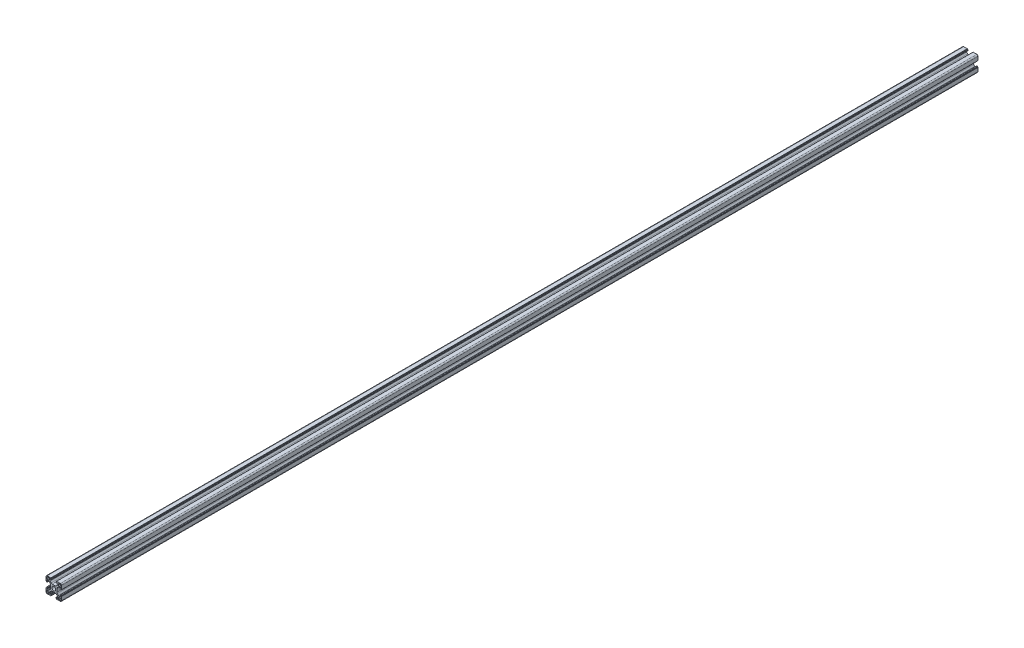
SolidWorks part; units mm, degrees
material "1060 Сплав"
ref_plane "Спереди" through (0, 0, 0) normal (0, 0, 1) x (1, 0, 0)
ref_plane "Сверху" through (0, 0, 0) normal (0, 1, 0) x (1, 0, 0)
ref_plane "Справа" through (0, 0, 0) normal (1, 0, 0) x (0, 0, -1)
sketch "Эскиз1" plane through (0, 0, 0) normal (0, 0, 1) x (1, 0, 0)
  line L0 (9.3595, 9.1357) -> (6.3595, 6.1357) construction
  line L1 (0.2595, 4.0357) -> (2.1582, 4.0357)
  line L2 (0.2595, 0.0357) -> (10.2595, 10.0357) construction
  line L3 (7.8595, 7.6357) -> (6.3595, 9.1357) construction
  line L4 (3.5725, 4.6215) -> (4.8737, 5.9227)
  line L5 (7.1595, 6.1357) -> (8.5595, 6.1357)
  line L6 (6.3595, 6.9357) -> (6.3595, 8.3357)
  line L7 (8.5595, 9.1357) -> (7.1595, 9.1357)
  line L8 (5.4595, 8.2357) -> (5.4595, 7.3369)
  line L9 (4.0227, 8.1089) -> (4.503, 8.5893)
  line L10 (3.4595, 9.5848) -> (3.9595, 9.5848)
  line L11 (3.8459, 8.0357) -> (3.5595, 8.0357)
  line L12 (4.8566, 8.7357) -> (4.9595, 8.7357)
  line L13 (3.9595, 9.8857) -> (3.9595, 9.5848)
  line L14 (3.3095, 9.4348) -> (3.3095, 8.2857)
  line L15 (8.7595, 10.0357) -> (4.1095, 10.0357)
  line L16 (9.3595, 8.3357) -> (9.3595, 6.9357)
  line L17 (10.2595, 8.5357) -> (10.2595, 3.8857)
  line L18 (9.6585, 3.0857) -> (8.5095, 3.0857)
  line L19 (10.1095, 3.7357) -> (9.8085, 3.7357)
  line L20 (8.9595, 4.6328) -> (8.9595, 4.7357)
  line L21 (8.2595, 3.6221) -> (8.2595, 3.3357)
  line L22 (9.8085, 3.2357) -> (9.8085, 3.7357)
  line L23 (8.3327, 3.7989) -> (8.813, 4.2793)
  line L24 (8.4595, 5.2357) -> (7.5607, 5.2357)
  line L25 (4.8452, 3.3487) -> (6.1465, 4.6499)
  line L26 (4.2595, 0.0357) -> (4.2595, 1.9345)
  line L27 (4.2595, 0.0357) -> (4.2595, -1.8631)
  line L28 (4.8452, -3.2773) -> (6.1465, -4.5785)
  line L29 (6.3595, -6.8643) -> (6.3595, -8.2643)
  line L30 (7.1595, -6.0643) -> (8.5595, -6.0643)
  line L31 (9.3595, -8.2643) -> (9.3595, -6.8643)
  line L32 (8.4595, -5.1643) -> (7.5607, -5.1643)
  line L33 (8.3327, -3.7275) -> (8.813, -4.2079)
  line L34 (9.8085, -3.1643) -> (9.8085, -3.6643)
  line L35 (8.2595, -3.5507) -> (8.2595, -3.2643)
  line L36 (8.9595, -4.5614) -> (8.9595, -4.6643)
  line L37 (10.1095, -3.6643) -> (9.8085, -3.6643)
  line L38 (9.6585, -3.0143) -> (8.5095, -3.0143)
  line L39 (10.2595, -8.4643) -> (10.2595, -3.8143)
  line L40 (8.5595, -9.0643) -> (7.1595, -9.0643)
  line L41 (8.7595, -9.9643) -> (4.1095, -9.9643)
  line L42 (3.3095, -9.3634) -> (3.3095, -8.2143)
  line L43 (3.9595, -9.8143) -> (3.9595, -9.5134)
  line L44 (4.8566, -8.6643) -> (4.9595, -8.6643)
  line L45 (3.8459, -7.9643) -> (3.5595, -7.9643)
  line L46 (3.4595, -9.5134) -> (3.9595, -9.5134)
  line L47 (4.0227, -8.0375) -> (4.503, -8.5179)
  line L48 (5.4595, -8.1643) -> (5.4595, -7.2655)
  line L49 (3.5725, -4.5501) -> (4.8737, -5.8513)
  line L50 (0.2595, -3.9643) -> (2.1582, -3.9643)
  line L51 (9.3595, -9.0643) -> (6.3595, -6.0643) construction
  line L52 (0.2595, 0.0357) -> (10.2595, -9.9643) construction
  line L53 (7.8595, -7.5643) -> (9.3595, -6.0643) construction
  line L54 (0.2595, -3.9643) -> (-1.6393, -3.9643)
  line L55 (-3.0535, -4.5501) -> (-4.3548, -5.8513)
  line L56 (-6.6405, -6.0643) -> (-8.0405, -6.0643)
  line L57 (-5.8405, -6.8643) -> (-5.8405, -8.2643)
  line L58 (-8.0405, -9.0643) -> (-6.6405, -9.0643)
  line L59 (-4.9405, -8.1643) -> (-4.9405, -7.2655)
  line L60 (-3.5038, -8.0375) -> (-3.9841, -8.5179)
  line L61 (-2.9405, -9.5134) -> (-3.4405, -9.5134)
  line L62 (-3.327, -7.9643) -> (-3.0405, -7.9643)
  line L63 (-4.3376, -8.6643) -> (-4.4405, -8.6643)
  line L64 (-3.4405, -9.8143) -> (-3.4405, -9.5134)
  line L65 (-2.7905, -9.3634) -> (-2.7905, -8.2143)
  line L66 (-8.2405, -9.9643) -> (-3.5905, -9.9643)
  line L67 (-8.8405, -8.2643) -> (-8.8405, -6.8643)
  line L68 (-9.7405, -8.4643) -> (-9.7405, -3.8143)
  line L69 (-9.1396, -3.0143) -> (-7.9905, -3.0143)
  line L70 (-9.5905, -3.6643) -> (-9.2896, -3.6643)
  line L71 (-8.4405, -4.5614) -> (-8.4405, -4.6643)
  line L72 (-7.7405, -3.5507) -> (-7.7405, -3.2643)
  line L73 (-9.2896, -3.1643) -> (-9.2896, -3.6643)
  line L74 (-7.8138, -3.7275) -> (-8.2941, -4.2079)
  line L75 (-7.9405, -5.1643) -> (-7.0418, -5.1643)
  line L76 (-4.3263, -3.2773) -> (-5.6275, -4.5785)
  line L77 (-3.7405, 0.0357) -> (-3.7405, -1.8631)
  line L78 (-8.8405, -9.0643) -> (-5.8405, -6.0643) construction
  line L79 (0.2595, 0.0357) -> (-9.7405, -9.9643) construction
  line L80 (-7.3405, -7.5643) -> (-5.8405, -9.0643) construction
  line L81 (-3.7405, 0.0357) -> (-3.7405, 1.9345)
  line L82 (-4.3263, 3.3487) -> (-5.6275, 4.6499)
  line L83 (-5.8405, 6.9357) -> (-5.8405, 8.3357)
  line L84 (-6.6405, 6.1357) -> (-8.0405, 6.1357)
  line L85 (-8.8405, 8.3357) -> (-8.8405, 6.9357)
  line L86 (-7.9405, 5.2357) -> (-7.0418, 5.2357)
  line L87 (-7.8138, 3.7989) -> (-8.2941, 4.2793)
  line L88 (-9.2896, 3.2357) -> (-9.2896, 3.7357)
  line L89 (-7.7405, 3.6221) -> (-7.7405, 3.3357)
  line L90 (-8.4405, 4.6328) -> (-8.4405, 4.7357)
  line L91 (-9.5905, 3.7357) -> (-9.2896, 3.7357)
  line L92 (-9.1396, 3.0857) -> (-7.9905, 3.0857)
  line L93 (-9.7405, 8.5357) -> (-9.7405, 3.8857)
  line L94 (-8.0405, 9.1357) -> (-6.6405, 9.1357)
  line L95 (-8.2405, 10.0357) -> (-3.5905, 10.0357)
  line L96 (-2.7905, 9.4348) -> (-2.7905, 8.2857)
  line L97 (-3.4405, 9.8857) -> (-3.4405, 9.5848)
  line L98 (-4.3376, 8.7357) -> (-4.4405, 8.7357)
  line L99 (-3.327, 8.0357) -> (-3.0405, 8.0357)
  line L100 (-2.9405, 9.5848) -> (-3.4405, 9.5848)
  line L101 (-3.5038, 8.1089) -> (-3.9841, 8.5893)
  line L102 (-4.9405, 8.2357) -> (-4.9405, 7.3369)
  line L103 (-3.0535, 4.6215) -> (-4.3548, 5.9227)
  line L104 (0.2595, 4.0357) -> (-1.6393, 4.0357)
  line L105 (-11.5046, 0.0357) -> (11.7638, 0.0357) construction
  line L106 (-8.8405, 9.1357) -> (-5.8405, 6.1357) construction
  line L107 (0.2595, -12.0507) -> (0.2595, 10.7546) construction
  line L108 (0.2595, 0.0357) -> (-9.7405, 10.0357) construction
  line L109 (-7.3405, 7.6357) -> (-8.8405, 6.1357) construction
  arc A0 (9.3595, 8.3357) -> (8.5595, 9.1357) centre (8.5595, 8.3357) ccw
  arc A1 (7.1595, 9.1357) -> (6.3595, 8.3357) centre (7.1595, 8.3357) ccw
  arc A2 (7.1595, 6.1357) -> (6.3595, 6.9357) centre (7.1595, 6.9357) cw
  arc A3 (8.7595, 10.0357) -> (10.2595, 8.5357) centre (8.7595, 8.5357) cw
  arc A4 (3.4595, 9.5848) -> (3.3095, 9.4348) centre (3.4595, 9.4348) ccw
  arc A5 (4.1095, 10.0357) -> (3.9595, 9.8857) centre (4.1095, 9.8857) ccw
  arc A6 (3.8459, 8.0357) -> (4.0227, 8.1089) centre (3.8459, 8.2857) ccw
  arc A7 (3.5595, 8.0357) -> (3.3095, 8.2857) centre (3.5595, 8.2857) cw
  arc A8 (4.503, 8.5893) -> (4.8566, 8.7357) centre (4.8566, 8.2357) cw
  arc A9 (4.9595, 8.7357) -> (5.4595, 8.2357) centre (4.9595, 8.2357) cw
  arc A10 (2.7595, 0.0357) -> (0.2595, 2.5357) centre (0.2595, 0.0357) ccw
  arc A11 (2.1582, 4.0357) -> (3.5725, 4.6215) centre (2.1582, 6.0357) ccw
  arc A12 (5.4595, 7.3369) -> (4.8737, 5.9227) centre (3.4595, 7.3369) cw
  arc A13 (9.3595, 6.9357) -> (8.5595, 6.1357) centre (8.5595, 6.9357) cw
  arc A14 (8.9595, 4.7357) -> (8.4595, 5.2357) centre (8.4595, 4.7357) ccw
  arc A15 (8.813, 4.2793) -> (8.9595, 4.6328) centre (8.4595, 4.6328) ccw
  arc A16 (8.2595, 3.3357) -> (8.5095, 3.0857) centre (8.5095, 3.3357) ccw
  arc A17 (8.2595, 3.6221) -> (8.3327, 3.7989) centre (8.5095, 3.6221) cw
  arc A18 (10.2595, 3.8857) -> (10.1095, 3.7357) centre (10.1095, 3.8857) cw
  arc A19 (9.8085, 3.2357) -> (9.6585, 3.0857) centre (9.6585, 3.2357) cw
  arc A20 (7.5607, 5.2357) -> (6.1465, 4.6499) centre (7.5607, 3.2357) ccw
  arc A21 (4.2595, 1.9345) -> (4.8452, 3.3487) centre (6.2595, 1.9345) cw
  arc A22 (8.5595, -9.0643) -> (9.3595, -8.2643) centre (8.5595, -8.2643) ccw
  arc A23 (9.3595, -6.8643) -> (8.5595, -6.0643) centre (8.5595, -6.8643) ccw
  arc A24 (6.3595, -6.8643) -> (7.1595, -6.0643) centre (7.1595, -6.8643) cw
  arc A25 (10.2595, -8.4643) -> (8.7595, -9.9643) centre (8.7595, -8.4643) cw
  arc A26 (9.8085, -3.1643) -> (9.6585, -3.0143) centre (9.6585, -3.1643) ccw
  arc A27 (10.2595, -3.8143) -> (10.1095, -3.6643) centre (10.1095, -3.8143) ccw
  arc A28 (8.2595, -3.5507) -> (8.3327, -3.7275) centre (8.5095, -3.5507) ccw
  arc A29 (8.2595, -3.2643) -> (8.5095, -3.0143) centre (8.5095, -3.2643) cw
  arc A30 (8.813, -4.2079) -> (8.9595, -4.5614) centre (8.4595, -4.5614) cw
  arc A31 (8.9595, -4.6643) -> (8.4595, -5.1643) centre (8.4595, -4.6643) cw
  arc A32 (0.2595, -2.4643) -> (2.7595, 0.0357) centre (0.2595, 0.0357) ccw
  arc A33 (4.2595, -1.8631) -> (4.8452, -3.2773) centre (6.2595, -1.8631) ccw
  arc A34 (7.5607, -5.1643) -> (6.1465, -4.5785) centre (7.5607, -3.1643) cw
  arc A35 (7.1595, -9.0643) -> (6.3595, -8.2643) centre (7.1595, -8.2643) cw
  arc A36 (4.9595, -8.6643) -> (5.4595, -8.1643) centre (4.9595, -8.1643) ccw
  arc A37 (4.503, -8.5179) -> (4.8566, -8.6643) centre (4.8566, -8.1643) ccw
  arc A38 (3.5595, -7.9643) -> (3.3095, -8.2143) centre (3.5595, -8.2143) ccw
  arc A39 (3.8459, -7.9643) -> (4.0227, -8.0375) centre (3.8459, -8.2143) cw
  arc A40 (4.1095, -9.9643) -> (3.9595, -9.8143) centre (4.1095, -9.8143) cw
  arc A41 (3.4595, -9.5134) -> (3.3095, -9.3634) centre (3.4595, -9.3634) cw
  arc A42 (5.4595, -7.2655) -> (4.8737, -5.8513) centre (3.4595, -7.2655) ccw
  arc A43 (2.1582, -3.9643) -> (3.5725, -4.5501) centre (2.1582, -5.9643) cw
  arc A44 (-8.8405, -8.2643) -> (-8.0405, -9.0643) centre (-8.0405, -8.2643) ccw
  arc A45 (-6.6405, -9.0643) -> (-5.8405, -8.2643) centre (-6.6405, -8.2643) ccw
  arc A46 (-6.6405, -6.0643) -> (-5.8405, -6.8643) centre (-6.6405, -6.8643) cw
  arc A47 (-8.2405, -9.9643) -> (-9.7405, -8.4643) centre (-8.2405, -8.4643) cw
  arc A48 (-2.9405, -9.5134) -> (-2.7905, -9.3634) centre (-2.9405, -9.3634) ccw
  arc A49 (-3.5905, -9.9643) -> (-3.4405, -9.8143) centre (-3.5905, -9.8143) ccw
  arc A50 (-3.327, -7.9643) -> (-3.5038, -8.0375) centre (-3.327, -8.2143) ccw
  arc A51 (-3.0405, -7.9643) -> (-2.7905, -8.2143) centre (-3.0405, -8.2143) cw
  arc A52 (-3.9841, -8.5179) -> (-4.3376, -8.6643) centre (-4.3376, -8.1643) cw
  arc A53 (-4.4405, -8.6643) -> (-4.9405, -8.1643) centre (-4.4405, -8.1643) cw
  arc A54 (-2.2405, 0.0357) -> (0.2595, -2.4643) centre (0.2595, 0.0357) ccw
  arc A55 (-1.6393, -3.9643) -> (-3.0535, -4.5501) centre (-1.6393, -5.9643) ccw
  arc A56 (-4.9405, -7.2655) -> (-4.3548, -5.8513) centre (-2.9405, -7.2655) cw
  arc A57 (-8.8405, -6.8643) -> (-8.0405, -6.0643) centre (-8.0405, -6.8643) cw
  arc A58 (-8.4405, -4.6643) -> (-7.9405, -5.1643) centre (-7.9405, -4.6643) ccw
  arc A59 (-8.2941, -4.2079) -> (-8.4405, -4.5614) centre (-7.9405, -4.5614) ccw
  arc A60 (-7.7405, -3.2643) -> (-7.9905, -3.0143) centre (-7.9905, -3.2643) ccw
  arc A61 (-7.7405, -3.5507) -> (-7.8138, -3.7275) centre (-7.9905, -3.5507) cw
  arc A62 (-9.7405, -3.8143) -> (-9.5905, -3.6643) centre (-9.5905, -3.8143) cw
  arc A63 (-9.2896, -3.1643) -> (-9.1396, -3.0143) centre (-9.1396, -3.1643) cw
  arc A64 (-7.0418, -5.1643) -> (-5.6275, -4.5785) centre (-7.0418, -3.1643) ccw
  arc A65 (-3.7405, -1.8631) -> (-4.3263, -3.2773) centre (-5.7405, -1.8631) cw
  arc A66 (-8.0405, 9.1357) -> (-8.8405, 8.3357) centre (-8.0405, 8.3357) ccw
  arc A67 (-8.8405, 6.9357) -> (-8.0405, 6.1357) centre (-8.0405, 6.9357) ccw
  arc A68 (-5.8405, 6.9357) -> (-6.6405, 6.1357) centre (-6.6405, 6.9357) cw
  arc A69 (-9.7405, 8.5357) -> (-8.2405, 10.0357) centre (-8.2405, 8.5357) cw
  arc A70 (-9.2896, 3.2357) -> (-9.1396, 3.0857) centre (-9.1396, 3.2357) ccw
  arc A71 (-9.7405, 3.8857) -> (-9.5905, 3.7357) centre (-9.5905, 3.8857) ccw
  arc A72 (-7.7405, 3.6221) -> (-7.8138, 3.7989) centre (-7.9905, 3.6221) ccw
  arc A73 (-7.7405, 3.3357) -> (-7.9905, 3.0857) centre (-7.9905, 3.3357) cw
  arc A74 (-8.2941, 4.2793) -> (-8.4405, 4.6328) centre (-7.9405, 4.6328) cw
  arc A75 (-8.4405, 4.7357) -> (-7.9405, 5.2357) centre (-7.9405, 4.7357) cw
  arc A76 (0.2595, 2.5357) -> (-2.2405, 0.0357) centre (0.2595, 0.0357) ccw
  arc A77 (-3.7405, 1.9345) -> (-4.3263, 3.3487) centre (-5.7405, 1.9345) ccw
  arc A78 (-7.0418, 5.2357) -> (-5.6275, 4.6499) centre (-7.0418, 3.2357) cw
  arc A79 (-6.6405, 9.1357) -> (-5.8405, 8.3357) centre (-6.6405, 8.3357) cw
  arc A80 (-4.4405, 8.7357) -> (-4.9405, 8.2357) centre (-4.4405, 8.2357) ccw
  arc A81 (-3.9841, 8.5893) -> (-4.3376, 8.7357) centre (-4.3376, 8.2357) ccw
  arc A82 (-3.0405, 8.0357) -> (-2.7905, 8.2857) centre (-3.0405, 8.2857) ccw
  arc A83 (-3.327, 8.0357) -> (-3.5038, 8.1089) centre (-3.327, 8.2857) cw
  arc A84 (-3.5905, 10.0357) -> (-3.4405, 9.8857) centre (-3.5905, 9.8857) cw
  arc A85 (-2.9405, 9.5848) -> (-2.7905, 9.4348) centre (-2.9405, 9.4348) cw
  arc A86 (-4.9405, 7.3369) -> (-4.3548, 5.9227) centre (-2.9405, 7.3369) ccw
  arc A87 (-1.6393, 4.0357) -> (-3.0535, 4.6215) centre (-1.6393, 6.0357) cw
  point P0 (0.2595, 0.0357)
  point P9 (0.2595, 0.0357)
  point P40 (8.9595, 3.7357)
  point P93 (3.9595, -8.6643)
  point P144 (3.9595, 8.7357)
  point P152 (8.9595, -3.6643)
  point P153 (0.2595, -3.8886)
  point P154 (0.2595, 0.0357)
  point P189 (-8.4405, -3.6643)
  point P228 (-3.4405, -8.6643)
  point P229 (-3.6648, 0.0357)
  point P230 (0.2595, 0.0357)
  point P268 (-3.4405, 8.7357)
  point P273 (4.1837, 0.0357)
  point P306 (-8.4405, 3.7357)
  point P307 (0.2595, 3.96)
  point P309 (0.2595, 0.0357)
  dimension "D3" = 5
  dimension "D6" = 2
  dimension "D1" = 2
  dimension "D2" = 6
  dimension "D4" = 4
  dimension "D5" = 0.9
extrude "Бобышка-Вытянуть1" add sketch "Эскиз1" along normal blind 1180
